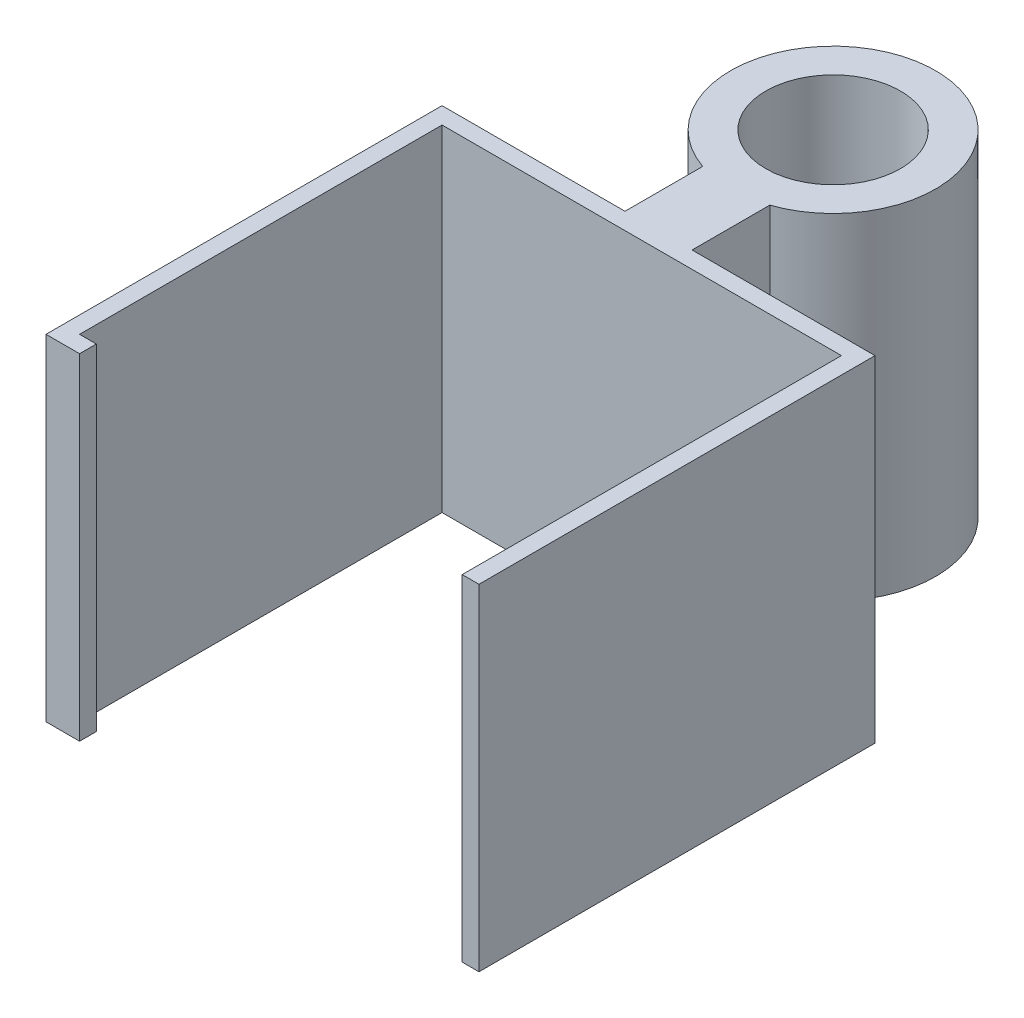
SolidWorks part; units mm, degrees
ref_plane "Front Plane" through (0, 0, 0) normal (0, 0, 1) x (1, 0, 0)
ref_plane "Top Plane" through (0, 0, 0) normal (0, 1, 0) x (1, 0, 0)
ref_plane "Right Plane" through (0, 0, 0) normal (1, 0, 0) x (0, 0, -1)
sketch "Sketch3" plane through (0, 0, 0) normal (0, 1, 0) x (1, 0, 0)
  line L1 (-6.45, 5.9) -> (6.45, 5.9)
  line L2 (-6.45, 5.9) -> (-6.45, -5.9)
  line L3 (-6.45, -5.9) -> (6.45, -5.9)
  line L4 (6.45, 5.9) -> (6.45, -5.9)
  line L5 (-6.45, 5.9) -> (6.45, -5.9) construction
  line L6 (-6.45, -5.9) -> (6.45, 5.9) construction
  point P0 (0, 0)
  dimension "D1" = 12.9
  dimension "D2" = 11.8
extrude "Boss-Extrude2" add sketch "Sketch3" along normal blind 10 contours L2 L3 L4 L1
sketch "Sketch4" plane through (0, 0, 0) normal (0, 1, 0) x (1, 0, 0)
  line L1 (-5.95, 5.4) -> (5.95, 5.4)
  line L2 (-5.95, 5.4) -> (-5.95, -5.4)
  line L3 (-5.95, -5.4) -> (5.95, -5.4)
  line L4 (5.95, 5.4) -> (5.95, -5.4)
  line L5 (-5.95, 5.4) -> (5.95, -5.4) construction
  line L6 (-5.95, -5.4) -> (5.95, 5.4) construction
  point P0 (0, 0)
  dimension "D1" = 11.9
  dimension "D2" = 10.8
extrude "Cut-Extrude1" cut sketch "Sketch4" along normal blind 10
sketch "Sketch5" plane through (0, 0, 0) normal (0, 1, 0) x (1, 0, 0)
  line L0 (5.95, -5.4) -> (5.95, 5.4) construction
  line L1 (5.95, 0) -> (-5.449, 0)
  line L2 (5.95, 0) -> (5.95, -5.9)
  line L3 (5.95, -5.9) -> (-5.449, -5.9)
  line L4 (-5.449, 0) -> (-5.449, -5.9)
  line L5 (-6.45, -5.9) -> (6.45, -5.9) construction
extrude "Cut-Extrude2" cut sketch "Sketch5" along normal blind 10 contours L1 L4 L3 L2
sketch "Sketch6" plane through (0, 0, 0) normal (0, 1, 0) x (1, 0, 0)
  line L0 (5.95, 5.4) -> (-5.95, 5.4) construction
  line L1 (-0.9993, 8.2425) -> (0.9993, 8.2425)
  line L2 (-0.9993, 8.2425) -> (-0.9993, 5.4)
  line L3 (-0.9993, 5.4) -> (0.9993, 5.4)
  line L4 (0.9993, 8.2425) -> (0.9993, 5.4)
  line L5 (-0.9993, 8.2425) -> (0.9993, 5.4) construction
  line L6 (-0.9993, 5.4) -> (0.9993, 8.2425) construction
  point P0 (0, 6.8212)
extrude "Boss-Extrude3" add sketch "Sketch6" along normal blind 10 contours L2 L3 L4 L1
sketch "Sketch7" plane through (0, 0, 0) normal (0, 1, 0) x (1, 0, 0)
  circle A0 centre (0, 11.1016) radius 3.0549
extrude "Boss-Extrude4" add sketch "Sketch7" along normal blind 10 contours A0
sketch "Sketch8" plane through (0, 0, 0) normal (0, 1, 0) x (1, 0, 0)
  circle A0 centre (0, 11.1016) radius 2.0064
extrude "Cut-Extrude3" cut sketch "Sketch8" along normal blind 10 contours A0
